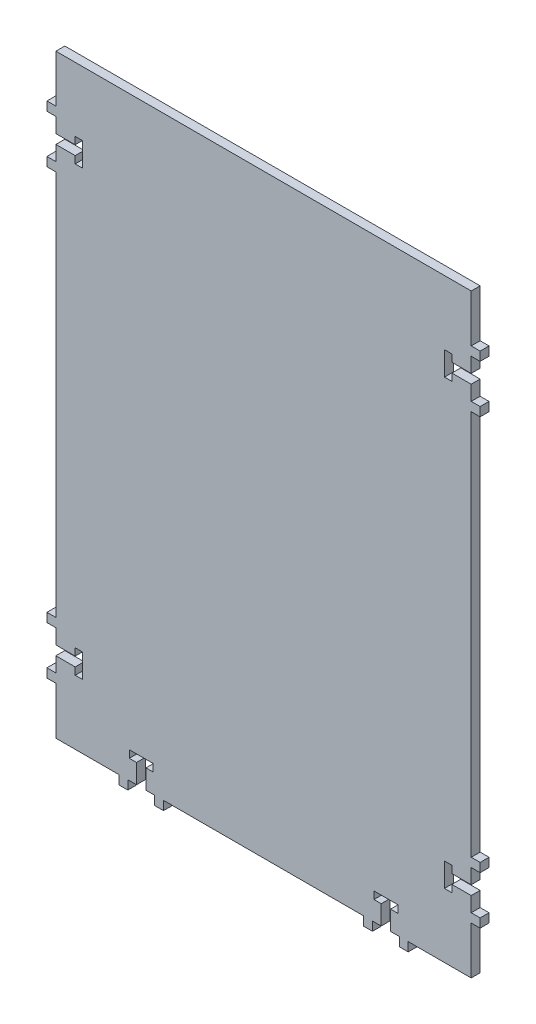
SolidWorks part; units mm, degrees
ref_plane "Front Plane" through (0, 0, 0) normal (0, 0, 1) x (1, 0, 0)
ref_plane "Top Plane" through (0, 0, 0) normal (0, 1, 0) x (1, 0, 0)
ref_plane "Right Plane" through (0, 0, 0) normal (1, 0, 0) x (0, 0, -1)
sketch "Sketch1" plane through (0, 0, 0) normal (0, 0, 1) x (1, 0, 0)
  line L0 (0, 27.15) -> (0, 32.15)
  line L1 (0, 32.15) -> (-3, 32.15)
  line L2 (69.805, 45) -> (69.805, 0) construction
  line L3 (-3, 32.15) -> (-3, 35.15)
  line L4 (0, 27.15) -> (6.5, 27.15)
  line L5 (6.5, 27.15) -> (6.5, 29.575)
  line L6 (6.5, 29.575) -> (9, 29.575)
  line L7 (9, 29.575) -> (9, 21.575)
  line L8 (9, 21.575) -> (6.5, 21.575)
  line L9 (6.5, 21.575) -> (6.5, 24)
  line L10 (6.5, 24) -> (0, 24)
  line L11 (0, 19) -> (0, 24)
  line L12 (0, 100) -> (-11.7068, 100) construction
  line L13 (-3, 35.15) -> (0, 35.15)
  line L14 (0, 35.15) -> (0, 164.85)
  line L15 (27.11, 0) -> (24.185, 0)
  line L16 (0, 184) -> (0, 200)
  line L17 (-3, 181) -> (0, 181)
  line L18 (-3, 184) -> (-3, 181)
  line L19 (0, 184) -> (-3, 184)
  line L20 (0, 200) -> (139.61, 200)
  line L21 (-3, 164.85) -> (0, 164.85)
  line L22 (0, 181) -> (0, 176)
  line L23 (6.5, 176) -> (0, 176)
  line L24 (6.5, 178.425) -> (6.5, 176)
  line L25 (9, 178.425) -> (6.5, 178.425)
  line L26 (9, 170.425) -> (9, 178.425)
  line L27 (6.5, 170.425) -> (9, 170.425)
  line L28 (6.5, 172.85) -> (6.5, 170.425)
  line L29 (0, 172.85) -> (6.5, 172.85)
  line L30 (-3, 167.85) -> (-3, 164.85)
  line L31 (0, 167.85) -> (-3, 167.85)
  line L32 (0, 172.85) -> (0, 167.85)
  line L33 (139.61, 16) -> (139.61, 0)
  line L34 (142.61, 19) -> (139.61, 19)
  line L35 (142.61, 16) -> (142.61, 19)
  line L36 (139.61, 16) -> (142.61, 16)
  line L37 (139.61, 172.85) -> (139.61, 167.85)
  line L38 (0, 16) -> (-3, 16)
  line L39 (-3, 16) -> (-3, 19)
  line L40 (-3, 19) -> (0, 19)
  line L41 (0, 16) -> (0, 0)
  line L42 (139.61, 167.85) -> (142.61, 167.85)
  line L43 (142.61, 167.85) -> (142.61, 164.85)
  line L44 (139.61, 172.85) -> (133.11, 172.85)
  line L45 (133.11, 172.85) -> (133.11, 170.425)
  line L46 (133.11, 170.425) -> (130.61, 170.425)
  line L47 (130.61, 170.425) -> (130.61, 178.425)
  line L48 (130.61, 178.425) -> (133.11, 178.425)
  line L49 (133.11, 178.425) -> (133.11, 176)
  line L50 (133.11, 176) -> (139.61, 176)
  line L51 (139.61, 181) -> (139.61, 176)
  line L52 (142.61, 164.85) -> (139.61, 164.85)
  line L53 (139.61, 184) -> (142.61, 184)
  line L54 (142.61, 184) -> (142.61, 181)
  line L55 (142.61, 181) -> (139.61, 181)
  line L56 (139.61, 184) -> (139.61, 200)
  line L57 (139.61, 35.15) -> (139.61, 164.85)
  line L58 (142.61, 35.15) -> (139.61, 35.15)
  line L59 (139.61, 19) -> (139.61, 24)
  line L60 (133.11, 24) -> (139.61, 24)
  line L61 (133.11, 21.575) -> (133.11, 24)
  line L62 (130.61, 21.575) -> (133.11, 21.575)
  line L63 (130.61, 29.575) -> (130.61, 21.575)
  line L64 (133.11, 29.575) -> (130.61, 29.575)
  line L65 (133.11, 27.15) -> (133.11, 29.575)
  line L66 (139.61, 27.15) -> (133.11, 27.15)
  line L67 (142.61, 32.15) -> (142.61, 35.15)
  line L68 (139.61, 32.15) -> (142.61, 32.15)
  line L69 (139.61, 27.15) -> (139.61, 32.15)
  line L70 (28.685, 0) -> (28.685, 11.6241) construction
  line L71 (27.11, 0) -> (27.11, 6.5)
  line L72 (27.11, 6.5) -> (24.685, 6.5)
  line L73 (24.685, 6.5) -> (24.685, 9)
  line L74 (24.685, 9) -> (32.685, 9)
  line L75 (32.685, 9) -> (32.685, 6.5)
  line L76 (32.685, 6.5) -> (30.26, 6.5)
  line L77 (30.26, 6.5) -> (30.26, 0)
  line L78 (24.185, 0) -> (24.185, -3)
  line L79 (110.925, 0) -> (110.925, 11.6241) construction
  line L80 (109.35, 6.5) -> (109.35, 0)
  line L81 (106.925, 6.5) -> (109.35, 6.5)
  line L82 (106.925, 9) -> (106.925, 6.5)
  line L83 (114.925, 9) -> (106.925, 9)
  line L84 (114.925, 6.5) -> (114.925, 9)
  line L85 (112.5, 6.5) -> (114.925, 6.5)
  line L86 (112.5, 0) -> (112.5, 6.5)
  line L87 (24.185, -3) -> (21.185, -3)
  line L88 (21.185, -3) -> (21.185, 0)
  line L89 (21.185, 0) -> (0, 0)
  line L90 (30.26, 0) -> (33.185, 0)
  line L91 (33.185, 0) -> (33.185, -3)
  line L92 (33.185, -3) -> (36.185, -3)
  line L93 (36.185, -3) -> (36.185, 0)
  line L94 (36.185, 0) -> (103.425, 0)
  line L95 (103.425, -3) -> (103.425, 0)
  line L96 (106.425, -3) -> (103.425, -3)
  line L97 (106.425, 0) -> (106.425, -3)
  line L98 (109.35, 0) -> (106.425, 0)
  line L99 (112.5, 0) -> (115.425, 0)
  line L100 (115.425, 0) -> (115.425, -3)
  line L101 (115.425, -3) -> (118.425, -3)
  line L102 (118.425, -3) -> (118.425, 0)
  line L103 (118.425, 0) -> (139.61, 0)
  point P20 (0, 100)
  point P24 (0, 100)
  point P29 (0, 100)
  point P63 (69.805, 200)
  point P64 (69.805, 200)
  point P67 (69.805, 0)
  point P68 (69.805, 0)
  point P80 (139.61, 100)
  point P92 (28.685, 9)
  point P97 (69.805, 0)
  point P112 (0, 0)
  point P113 (25.6475, 0)
  point P114 (28.685, 0)
  point P115 (28.6644, 1.088)
  point P116 (0, 0)
  point P117 (0, 0)
  point P118 (0, 0)
  point P120 (69.805, 0)
  dimension "D2" = 5
  dimension "D3" = 3.15
  dimension "D4" = 8
  dimension "D5" = 2.5
  dimension "D6" = 16
  dimension "D7" = 3
  dimension "D8" = 3
  dimension "D9" = 3
  dimension "D10" = 5
  dimension "D11" = 9
  dimension "D12" = 3
  dimension "D13" = 3
  dimension "D14" = 28.685
  dimension "D15" = 4.5
  dimension "D16" = 3
  dimension "D17" = 69.805
  dimension "D18" = 3.15
  dimension "D19" = 1.575
  dimension "D20" = 8
  dimension "D21" = 2.5
  dimension "D22" = 2.5
  dimension "D23" = 3
  dimension "D24" = 3
  dimension "D25" = 4.5
  dimension "D26" = 3
  dimension "D27" = 3
  dimension "D28" = 9
  dimension "D29" = 11.6241
extrude "Boss-Extrude1" add sketch "Sketch1" against normal blind 3
